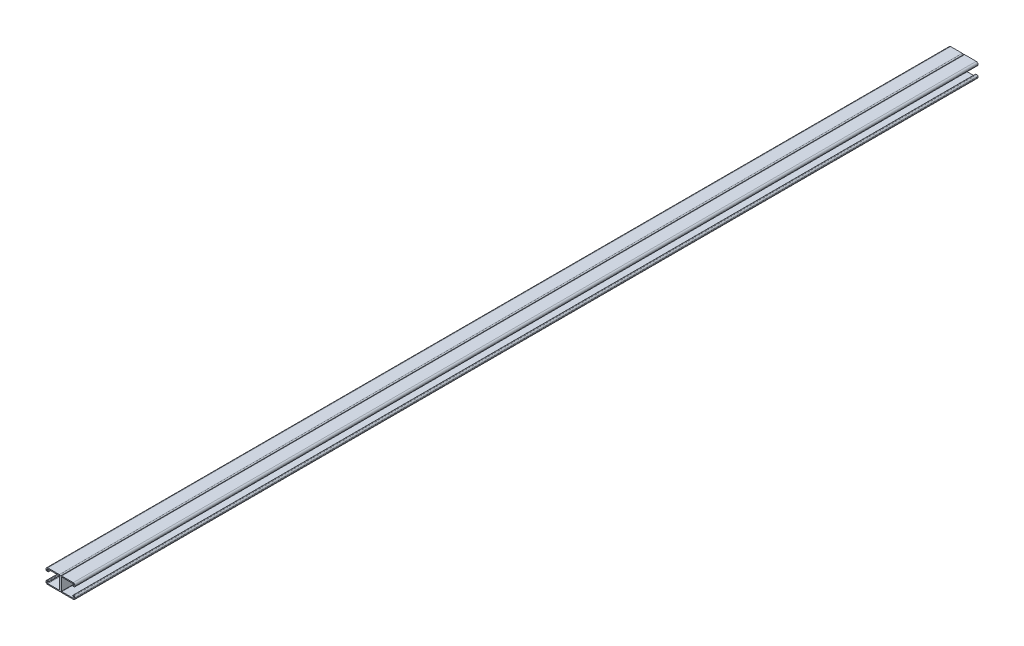
SolidWorks part; units mm, degrees
ref_plane "Front Plane" through (0, 0, 0) normal (0, 0, 1) x (1, 0, 0)
ref_plane "Top Plane" through (0, 0, 0) normal (0, 1, 0) x (1, 0, 0)
ref_plane "Right Plane" through (0, 0, 0) normal (1, 0, 0) x (0, 0, -1)
sketch "Sketch1" plane through (0, 0, 0) normal (0, 0, 1) x (1, 0, 0)
  line L0 (0, 0) -> (-41.275, 0) construction
  line L3 (-41.275, 20.6375) -> (0, 20.6375) construction
  line L4 (-41.275, 20.6375) -> (-41.275, -20.6375) construction
  line L5 (-41.275, -20.6375) -> (0, -20.6375) construction
  line L6 (0, 20.6375) -> (0, -20.6375) construction
  line L7 (-36.2267, 20.6375) -> (-3.4607, 20.6375)
  line L8 (0, 17.1767) -> (0, -17.1767)
  line L9 (-2.794, -17.1767) -> (-2.794, 17.1767)
  line L10 (-3.4608, 17.8435) -> (-36.2267, 17.8435)
  line L11 (-41.275, 15.5892) -> (-41.275, 14.5732)
  line L12 (-37.8142, 11.1125) -> (-35.5346, 11.1125)
  line L14 (-35.5346, 13.9065) -> (-37.8142, 13.9065)
  line L15 (-38.481, 14.5732) -> (-38.481, 15.5892)
  line L16 (-38.481, -14.5733) -> (-38.481, -15.5893)
  line L17 (-35.5346, -13.9065) -> (-37.8142, -13.9065)
  line L18 (-37.8142, -11.1125) -> (-35.5346, -11.1125)
  line L19 (-41.275, -15.5893) -> (-41.275, -14.5733)
  line L20 (-3.4607, -17.8435) -> (-36.2267, -17.8435)
  line L21 (-36.2267, -20.6375) -> (-3.4607, -20.6375)
  line L22 (-2.794, -20.6375) -> (-2.794, 20.6375) construction
  arc A1 (0, 17.1767) -> (-3.4607, 20.6375) centre (-3.4607, 17.1767) ccw
  arc A2 (-2.794, 17.1767) -> (-3.4608, 17.8435) centre (-3.4607, 17.1767) ccw
  arc A4 (-36.2267, 20.6375) -> (-41.275, 15.5892) centre (-36.2267, 15.5892) ccw
  arc A5 (-41.275, 14.5732) -> (-37.8142, 11.1125) centre (-37.8142, 14.5732) ccw
  arc A6 (-35.5346, 11.1125) -> (-35.5346, 13.9065) centre (-35.5346, 12.5095) ccw
  arc A7 (-37.8142, 13.9065) -> (-38.481, 14.5732) centre (-37.8142, 14.5732) cw
  arc A8 (-38.481, 15.5892) -> (-36.2267, 17.8435) centre (-36.2267, 15.5892) cw
  arc A9 (-38.481, -15.5893) -> (-36.2267, -17.8435) centre (-36.2267, -15.5893) ccw
  arc A10 (-37.8142, -13.9065) -> (-38.481, -14.5733) centre (-37.8142, -14.5733) ccw
  arc A11 (-35.5346, -11.1125) -> (-35.5346, -13.9065) centre (-35.5346, -12.5095) cw
  arc A12 (-41.275, -14.5733) -> (-37.8142, -11.1125) centre (-37.8142, -14.5733) cw
  arc A13 (-36.2267, -20.6375) -> (-41.275, -15.5893) centre (-36.2267, -15.5893) cw
  arc A14 (-2.794, -17.1767) -> (-3.4607, -17.8435) centre (-3.4607, -17.1767) cw
  arc A15 (0, -17.1767) -> (-3.4607, -20.6375) centre (-3.4607, -17.1767) cw
  point P24 (0, 20.6375)
  point P65 (-2.794, 0)
  dimension "D1" = 3.4608
  dimension "D2" = 5.0482
  dimension "D3" = 3.4608
  dimension "Ht." = 41.275
  dimension "Wd." = 41.275
  dimension "Thk." = 2.794
  dimension "D4" = 9.525
  dimension "D5" = 7.1374
extrude "Boss-Extrude1" add sketch "Sketch1" against normal blind 3048
sketch "Sketch3" plane through (0, 0, 0) normal (1, 0, 0) x (0, 0, -1)
  line L0 (0, 0) -> (3048, 0) construction
  point P2 (101.6, 0)
  point P3 (2946.4, 0)
  dimension "D1" = 101.6
  dimension "D2" = 101.6
  dimension "D3" = 3048
mirror "Mirror1" about plane through (0, 17.1767, -3048) normal (1, 0, 0) of bodies 114
sketch "Sketch4" plane through (0, -20.6375, 0) normal (0, -1, 0) x (1, 0, 0)
  line L0 (3.4608, -3048) -> (3.4608, -485.775) construction
  line L1 (41.275, 0) -> (-41.275, 0)
  line L2 (41.275, 0) -> (41.275, -485.775)
  line L3 (41.275, -485.775) -> (-41.275, -485.775)
  line L4 (-41.275, 0) -> (-41.275, -485.775)
  dimension "D1" = 2562.225
extrude "Cut-Extrude1" cut sketch "Sketch4" against normal through all
combine bodies "Combine1" operation type add bodies to combine 119 118
equation "\"D3@Sketch3\" = \"Lg.@Boss-Extrude1\""
